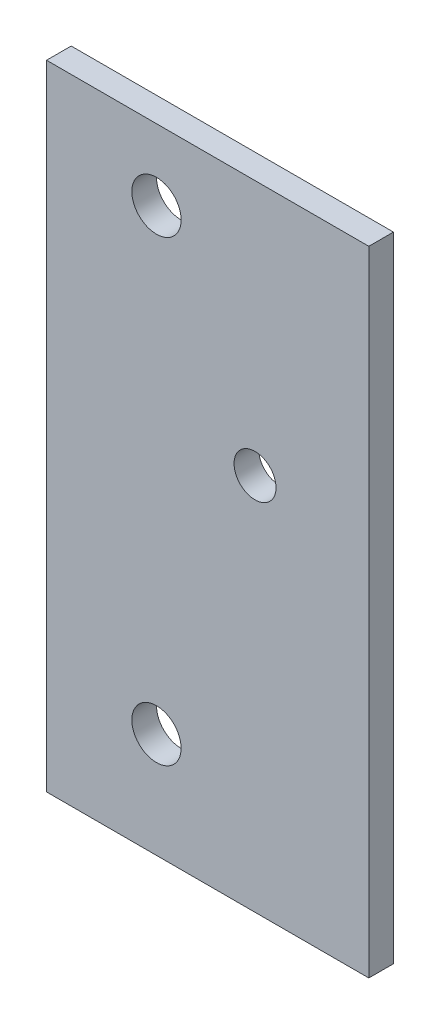
SolidWorks part; units mm, degrees
ref_plane "Front Plane" through (0, 0, 0) normal (0, 0, 1) x (1, 0, 0)
ref_plane "Top Plane" through (0, 0, 0) normal (0, 1, 0) x (1, 0, 0)
ref_plane "Right Plane" through (0, 0, 0) normal (1, 0, 0) x (0, 0, -1)
sketch "Sketch1" plane through (0, 0, 0) normal (0, 0, 1) x (1, 0, 0)
  line L2 (-90.3649, -249.3918) -> (-48.8384, -249.3918)
  line L3 (-90.3649, -249.3918) -> (-90.3649, -167.7349)
  line L4 (-90.3649, -167.7349) -> (-48.8384, -167.7349)
  line L5 (-48.8384, -249.3918) -> (-48.8384, -167.7349)
  circle A0 centre (-76.2, -176.8929) radius 3.175
  circle A1 centre (-76.2, -235.8571) radius 3.175
  dimension "D1" = 6.35
  dimension "D2" = 6.35
  dimension "D3" = 81.6569
  dimension "D4" = 41.5266
  dimension "D5" = 9.158
  dimension "D6" = 14.1649
extrude "Boss-Extrude1" add sketch "Sketch1" along normal blind 3.175
hole_wizard "1/4-28 Tapped Hole1" positions "Sketch4" profile "Sketch3" tap size "1/4-28" standard "ANSI Inch" end condition through all
sketch "Sketch4" plane through (0, 0, 3.175) normal (0, 0, 1) x (1, 0, 0)
  point P0 (-63.5, -200.66)
sketch "Sketch3" plane through (-63.5, -200.66, 3.175) normal (1, 0, 0) x (0, -1, 0)
  line L0 (0, 0) -> (0, 3.175)
  line L1 (0, 3.175) -> (2.7051, 3.175)
  line L2 (2.7051, 3.175) -> (2.7051, 0)
  line L5 (2.7051, 0) -> (0, 0)
  line L11 (0, -6.35) -> (0, 107.95) construction
  dimension "Thru Tap Drill Dia." = 5.4102
  dimension "Thru Tap Drill Depth" = 3.175
